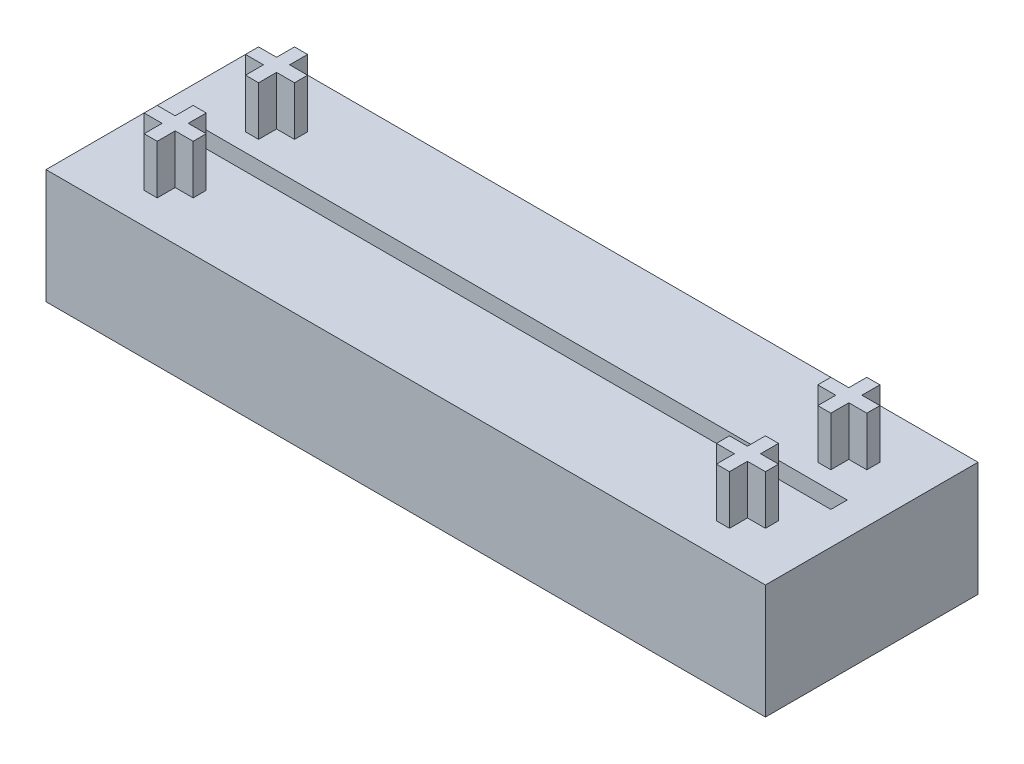
SolidWorks part; units mm, degrees
ref_plane "Přední rovina" through (0, 0, 0) normal (0, 0, 1) x (1, 0, 0)
ref_plane "Horní rovina" through (0, 0, 0) normal (0, 1, 0) x (1, 0, 0)
ref_plane "Pravá rovina" through (0, 0, 0) normal (1, 0, 0) x (0, 0, -1)
sketch "Skica1" plane through (0, 0, 0) normal (0, 1, 0) x (1, 0, 0)
  line L1 (0, 0) -> (220, 0)
  line L2 (0, 0) -> (0, 65)
  line L3 (0, 65) -> (220, 65)
  line L4 (220, 0) -> (220, 65)
  line L5 (10, 30) -> (210, 30)
  line L6 (10, 30) -> (10, 35)
  line L7 (10, 35) -> (210, 35)
  line L8 (210, 30) -> (210, 35)
  dimension "D1" = 65
  dimension "D2" = 220
  dimension "D3" = 30
  dimension "D4" = 30
  dimension "D5" = 10
  dimension "D6" = 10
extrude "Přidat vysunutím1" add sketch "Skica1" along normal blind 35
sketch "Skica2" plane through (0, 35, 0) normal (0, 1, 0) x (1, 0, 0)
  line L4 (24.5, 46) -> (30, 46)
  line L5 (20.5, 55.5) -> (24.5, 55.5)
  line L6 (20.5, 55.5) -> (20.5, 50)
  line L7 (20.5, 40.5) -> (24.5, 40.5)
  line L8 (24.5, 55.5) -> (24.5, 50)
  line L9 (15, 50) -> (20.5, 50)
  line L10 (15, 50) -> (15, 46)
  line L11 (15, 46) -> (20.5, 46)
  line L12 (30, 50) -> (30, 46)
  line L13 (20.5, 46) -> (20.5, 40.5)
  line L14 (24.5, 46) -> (24.5, 40.5)
  line L15 (24.5, 50) -> (30, 50)
  line L16 (0, 32.5) -> (220, 32.5) construction
  line L17 (0, 0) -> (220, 0) construction
  line L18 (0, 0) -> (0, 65) construction
  line L19 (0, 65) -> (220, 65) construction
  line L20 (220, 0) -> (220, 65) construction
  line L21 (15, 15) -> (15, 19)
  line L22 (110, 65) -> (110, 0) construction
  line L23 (15, 19) -> (20.5, 19)
  line L24 (20.5, 19) -> (20.5, 24.5)
  line L25 (20.5, 24.5) -> (24.5, 24.5)
  line L26 (24.5, 19) -> (24.5, 24.5)
  line L27 (24.5, 19) -> (30, 19)
  line L28 (30, 15) -> (30, 19)
  line L29 (24.5, 15) -> (30, 15)
  line L30 (24.5, 9.5) -> (24.5, 15)
  line L31 (20.5, 9.5) -> (24.5, 9.5)
  line L32 (20.5, 9.5) -> (20.5, 15)
  line L33 (15, 15) -> (20.5, 15)
  line L34 (205, 15) -> (199.5, 15)
  line L35 (199.5, 9.5) -> (199.5, 15)
  line L36 (199.5, 9.5) -> (195.5, 9.5)
  line L37 (195.5, 9.5) -> (195.5, 15)
  line L38 (195.5, 15) -> (190, 15)
  line L39 (190, 15) -> (190, 19)
  line L40 (195.5, 19) -> (190, 19)
  line L41 (195.5, 19) -> (195.5, 24.5)
  line L42 (199.5, 24.5) -> (195.5, 24.5)
  line L43 (199.5, 19) -> (199.5, 24.5)
  line L44 (205, 19) -> (199.5, 19)
  line L45 (205, 15) -> (205, 19)
  line L46 (205, 50) -> (205, 46)
  line L47 (205, 46) -> (199.5, 46)
  line L48 (199.5, 46) -> (199.5, 40.5)
  line L49 (199.5, 40.5) -> (195.5, 40.5)
  line L50 (195.5, 46) -> (195.5, 40.5)
  line L51 (195.5, 46) -> (190, 46)
  line L52 (190, 50) -> (190, 46)
  line L53 (195.5, 50) -> (190, 50)
  line L54 (195.5, 55.5) -> (195.5, 50)
  line L55 (199.5, 55.5) -> (195.5, 55.5)
  line L56 (199.5, 55.5) -> (199.5, 50)
  line L57 (205, 50) -> (199.5, 50)
  point P13 (22.5, 55.5)
  point P15 (30, 48)
  point P62 (0, 0)
  point P63 (0, 0)
  point P65 (220, 65)
  dimension "D1" = 4
  dimension "D2" = 15
  dimension "D3" = 15
  dimension "D4" = 15
extrude "Přidat vysunutím2" add sketch "Skica2" along normal blind 15 contours L21 L33 L32 L31 L30 L29 L28 L27 L26 L25 L24 L23 | L15 L8 L5 L6 L9 L10 L11 L13 L7 L14 L4 L12 | L46 L57 L56 L55 L54 L53 L52 L51 L50 L49 L48 L47 | L34 L45 L44 L43 L42 L41 L40 L39 L38 L37 L36 L35
